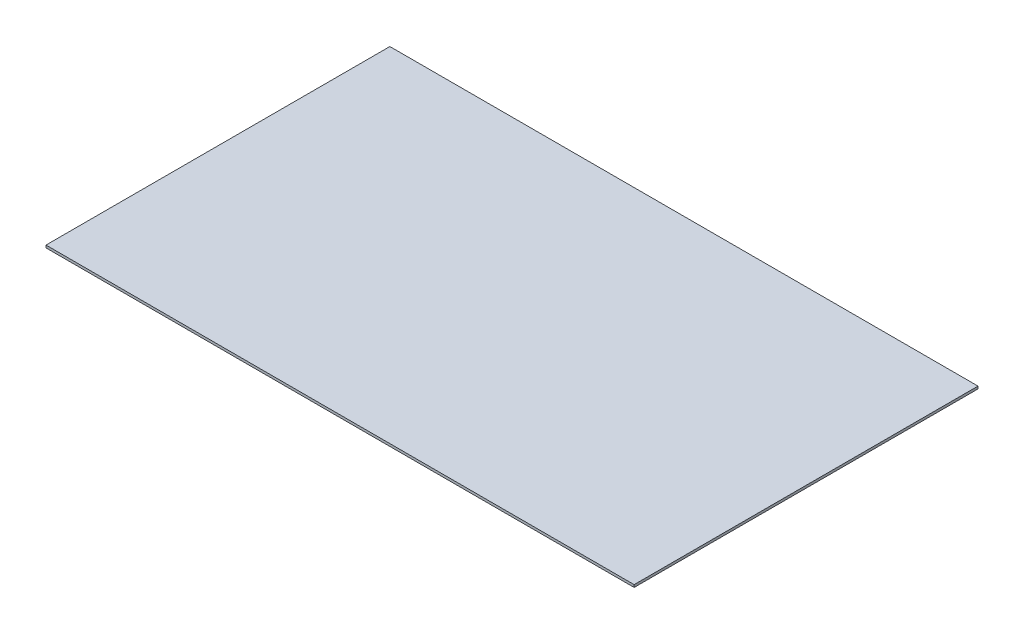
SolidWorks part; units mm, degrees
ref_plane "Спереди" through (0, 0, 0) normal (0, 0, 1) x (1, 0, 0)
ref_plane "Сверху" through (0, 0, 0) normal (0, 1, 0) x (1, 0, 0)
ref_plane "Справа" through (0, 0, 0) normal (1, 0, 0) x (0, 0, -1)
sketch "Эскиз1" plane through (0, 0, 0) normal (0, 1, 0) x (1, 0, 0)
  line L1 (1069, -625) -> (-1069, -625)
  line L2 (1069, -625) -> (1069, 625)
  line L3 (1069, 625) -> (-1069, 625)
  line L4 (-1069, -625) -> (-1069, 625)
  line L5 (1069, -625) -> (-1069, 625) construction
  line L6 (1069, 625) -> (-1069, -625) construction
  point P0 (0, 0)
  dimension "D1" = 2138
  dimension "D2" = 1250
extrude "Бобышка-Вытянуть1" add sketch "Эскиз1" along normal blind 9
